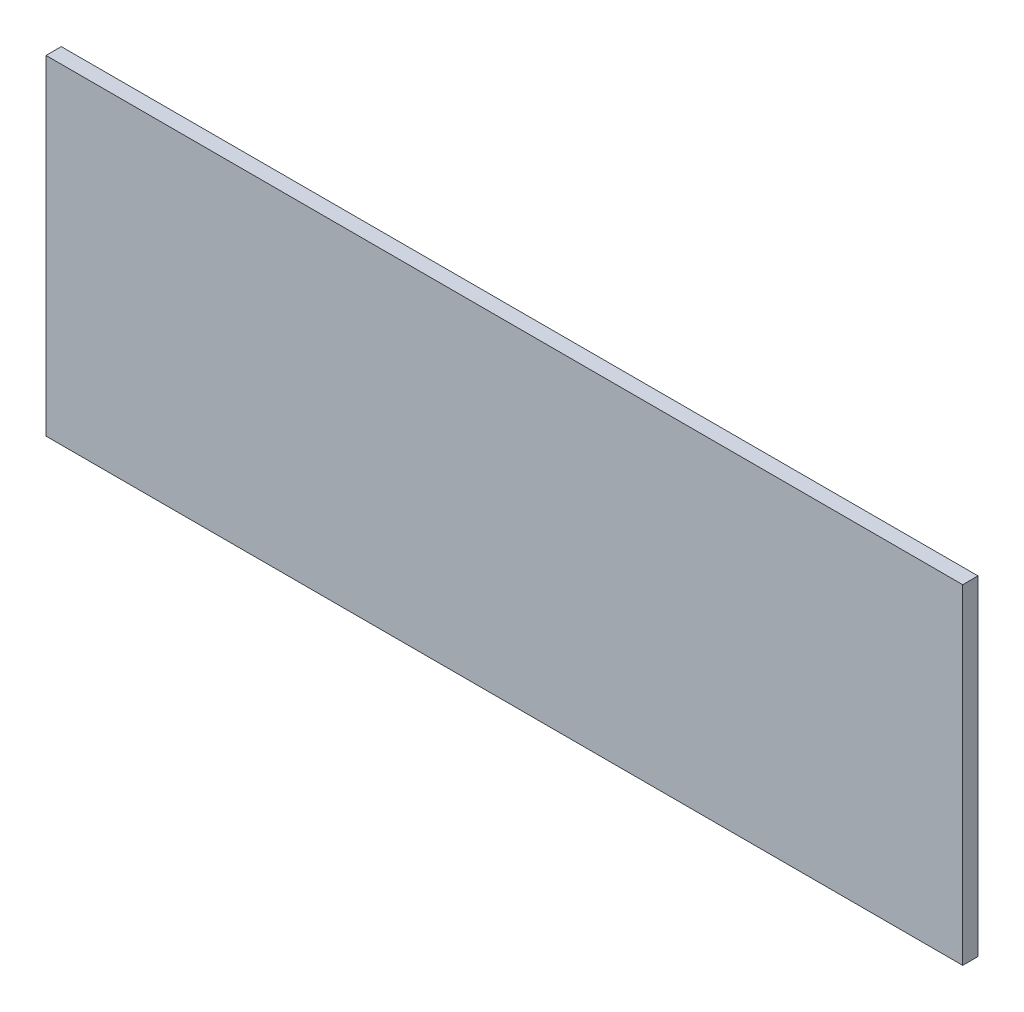
SolidWorks part; units mm, degrees
ref_plane "Plan de face" through (0, 0, 0) normal (0, 0, 1) x (1, 0, 0)
ref_plane "Plan de dessus" through (0, 0, 0) normal (0, 1, 0) x (1, 0, 0)
ref_plane "Plan de droite" through (0, 0, 0) normal (1, 0, 0) x (0, 0, -1)
sketch "Esquisse1" plane through (0, 0, 0) normal (0, 0, 1) x (1, 0, 0)
  line L1 (-17.9595, 11.7283) -> (42.0405, 11.7283)
  line L2 (-17.9595, 11.7283) -> (-17.9595, -9.8517)
  line L3 (-17.9595, -9.8517) -> (42.0405, -9.8517)
  line L4 (42.0405, 11.7283) -> (42.0405, -9.8517)
  dimension "D1" = 21.58
  dimension "D2" = 60
extrude "Boss.-Extru.1" add sketch "Esquisse1" along normal blind 1
